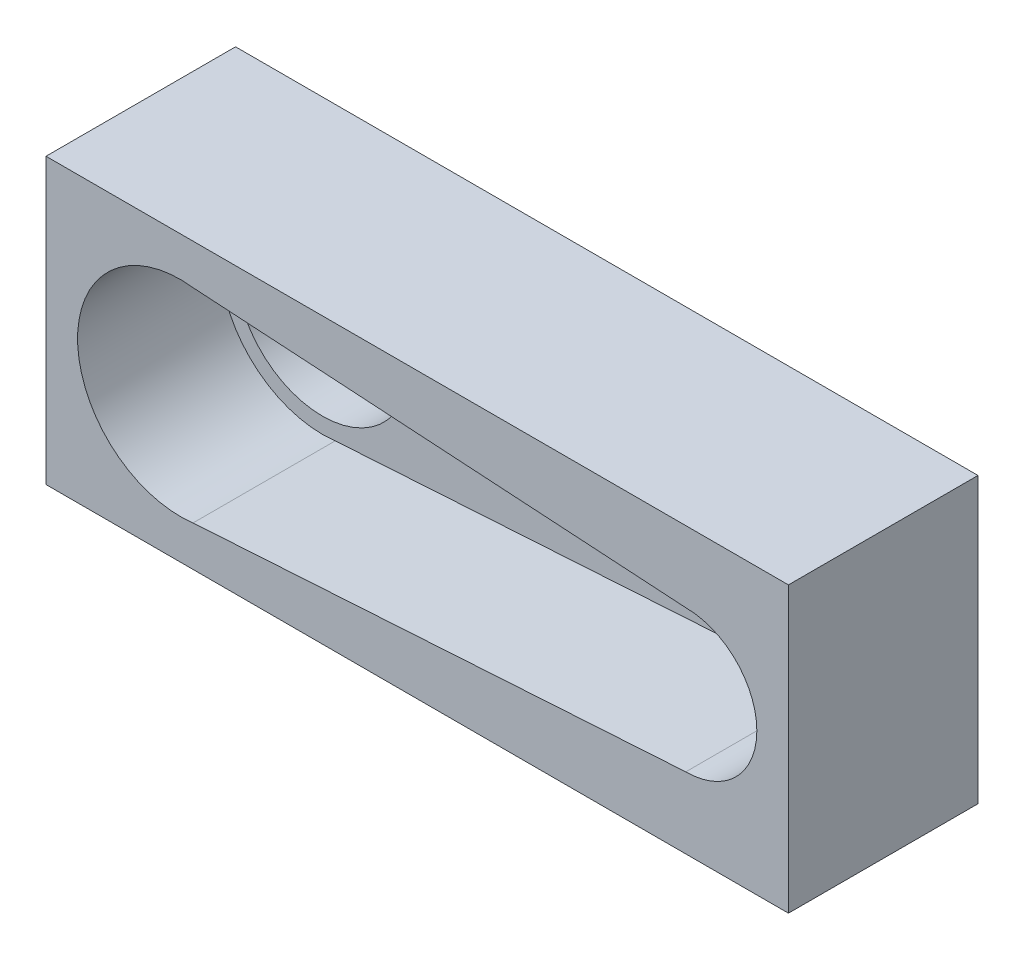
SolidWorks part; units mm, degrees
ref_plane "Plan de face" through (0, 0, 0) normal (0, 0, 1) x (1, 0, 0)
ref_plane "Plan de dessus" through (0, 0, 0) normal (0, 1, 0) x (1, 0, 0)
ref_plane "Plan de droite" through (0, 0, 0) normal (1, 0, 0) x (0, 0, -1)
sketch "Esquisse1" plane through (0, 0, 0) normal (0, 0, 1) x (1, 0, 0)
  line L0 (0, 0) -> (47, 0)
  line L1 (0, 0) -> (0, 18)
  line L2 (47, 0) -> (47, 18)
  line L3 (0, 18) -> (47, 18)
  line L4 (0, 9) -> (47, 9) construction
  line L5 (8.5, 15.5) -> (40.5, 13.5)
  line L6 (40.5, 13.5) -> (40.5, 4.5)
  line L7 (40.5, 4.5) -> (8.5, 2.5)
  line L8 (8.5, 2.5) -> (8.5, 15.5)
  circle A0 centre (8.5, 9) radius 6.5
  circle A1 centre (40.5, 9) radius 4.5
  circle A2 centre (31, 9) radius 0.75
  circle A3 centre (36.5, 9) radius 0.75
  circle A4 centre (42, 9) radius 0.75
  dimension "D3" = 13
  dimension "D4" = 9
  dimension "D5" = 8.5
  dimension "D10" = 1.5
  dimension "D11" = 1.5
  dimension "D12" = 1.5
  dimension "D1" = 18
  dimension "D2" = 47
  dimension "D6" = 32
  dimension "D7" = 1.5
  dimension "D8" = 5.5
  dimension "D9" = 5.5
extrude "Boss.-Extru.1" add sketch "Esquisse1" along normal blind 9 contours L1 L4 A0 L5 A1 L2 L3 | L4 L1 L0 L2 A1 L7 A0
sketch "Esquisse2" plane through (0, 0, 0) normal (0, 0, 1) x (1, 0, 0)
  line L0 (0, 0) -> (47, 0)
  line L1 (0, 0) -> (0, 18)
  line L2 (47, 0) -> (47, 18)
  line L3 (0, 18) -> (47, 18)
  line L4 (0, 9) -> (47, 9) construction
  line L5 (8.5, 15.5) -> (40.5, 13.5)
  line L6 (40.5, 13.5) -> (40.5, 4.5)
  line L7 (40.5, 4.5) -> (8.5, 2.5)
  line L8 (8.5, 2.5) -> (8.5, 15.5)
  circle A0 centre (8.5, 9) radius 6.5
  circle A1 centre (40.5, 9) radius 4.5
  circle A2 centre (31, 9) radius 0.75
  circle A3 centre (36.5, 9) radius 0.75
  circle A4 centre (42, 9) radius 0.75
  circle A5 centre (8.5, 9) radius 5.5
  dimension "D3" = 13
  dimension "D4" = 9
  dimension "D5" = 8.5
  dimension "D10" = 1.5
  dimension "D11" = 1.5
  dimension "D12" = 1.5
  dimension "D13" = 11
  dimension "D1" = 18
  dimension "D2" = 47
  dimension "D6" = 32
  dimension "D7" = 1.5
  dimension "D8" = 5.5
  dimension "D9" = 5.5
extrude "Boss.-Extru.2" add sketch "Esquisse2" against normal blind 3 contours L6 L4 A4 A1 | L4 L6 A1 A4 | L4 A3 A1 L6 | A3 L4 L6 A1 | A0 L4 A2 A3 A1 L5 | L4 A0 L7 A1 A3 A2 | A0 L4 L8 | L8 L4 A0 L5 | L4 L8 L7 A0 | L4 A0 L8 | L4 L1 L0 L2 A1 L7 A0 | L1 L4 A0 L5 A1 L2 L3
